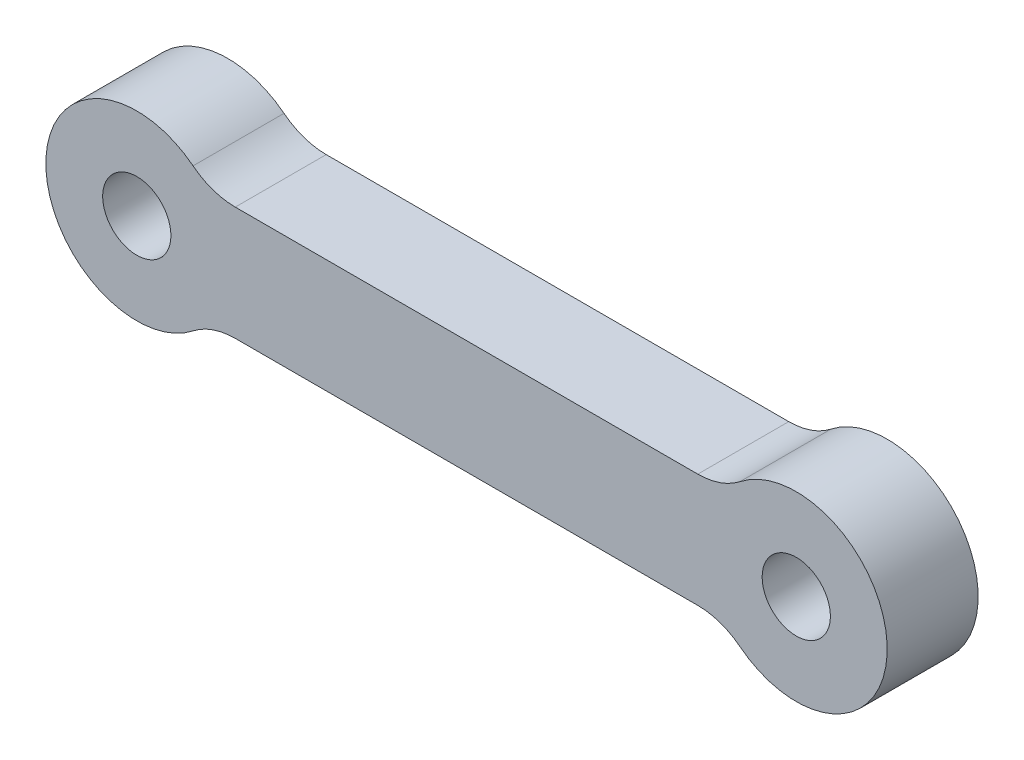
SolidWorks part; units mm, degrees
ref_plane "Front Plane" through (0, 0, 0) normal (0, 0, 1) x (1, 0, 0)
ref_plane "Top Plane" through (0, 0, 0) normal (0, 1, 0) x (1, 0, 0)
ref_plane "Right Plane" through (0, 0, 0) normal (1, 0, 0) x (0, 0, -1)
sketch "Sketch1" plane through (0, 0, 0) normal (0, 0, 1) x (1, 0, 0)
  line L0 (-14.5, 0) -> (14.5, 0) construction
  line L1 (0, 0) -> (0, 5.3443) construction
  line L3 (-10.1699, -2.5) -> (10.1699, -2.5)
  line L5 (-10.1699, 2.5) -> (10.1699, 2.5)
  line L7 (-11.3775, -2.5) -> (11.3775, 2.5) construction
  line L8 (-11.3775, 2.5) -> (11.3775, -2.5) construction
  circle A0 centre (-14.5, 0) radius 1.5
  arc A3 (-12.0256, 3.1429) -> (-12.0256, -3.1429) centre (-14.5, 0) ccw
  circle A4 centre (14.5, 0) radius 1.5
  arc A5 (12.0256, 3.1429) -> (12.0256, -3.1429) centre (14.5, 0) cw
  arc A6 (10.1699, -2.5) -> (12.0256, -3.1429) centre (10.1699, -5.5) cw
  arc A7 (10.1699, 2.5) -> (12.0256, 3.1429) centre (10.1699, 5.5) ccw
  arc A8 (-10.1699, -2.5) -> (-12.0256, -3.1429) centre (-10.1699, -5.5) ccw
  arc A9 (-12.0256, 3.1429) -> (-10.1699, 2.5) centre (-10.1699, 5.5) ccw
  point P4 (0, 0)
  dimension "D2" = 3
  dimension "D3" = 8
  dimension "D5" = 3
  dimension "D1" = 29
  dimension "D4" = 5
extrude "Boss-Extrude1" add sketch "Sketch1" along normal blind 4
